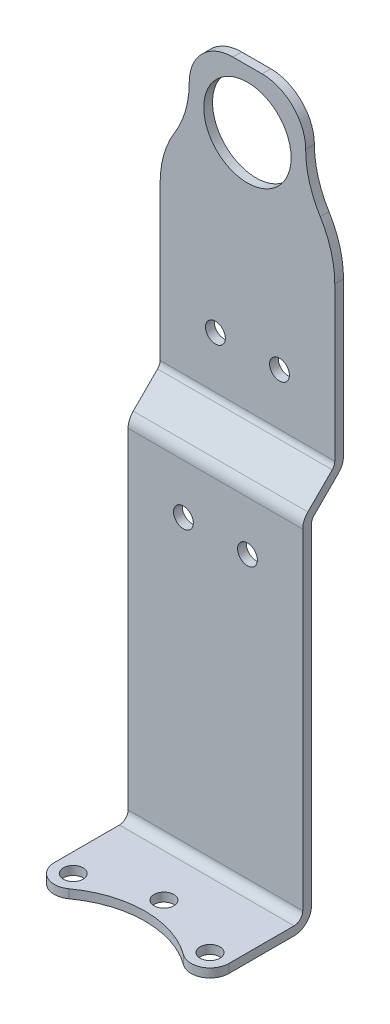
SolidWorks part; units mm, degrees
ref_plane "前视基准面" through (0, 0, 0) normal (0, 0, 1) x (1, 0, 0)
ref_plane "上视基准面" through (0, 0, 0) normal (0, 1, 0) x (1, 0, 0)
ref_plane "右视基准面" through (0, 0, 0) normal (1, 0, 0) x (0, 0, -1)
ref_plane "基准面1" through (0, -32, 0) normal (0, 1, 0) x (1, 0, 0)
sketch "草图1" plane through (0, -32, 0) normal (0, 1, 0) x (1, 0, 0)
  line L0 (-15, 4) -> (-15, -15.6773)
  line L1 (15, -15.6773) -> (15, 4)
  line L2 (15, 4) -> (-15, 4)
  arc A0 (-15, -15.6773) -> (-9.8358, -18.3038) centre (-11.75, -15.6773) ccw
  arc A1 (-9.8358, -18.3038) -> (9.8358, -18.3038) centre (0, -31.8) cw
  arc A2 (9.8358, -18.3038) -> (15, -15.6773) centre (11.75, -15.6773) ccw
extrude "凸台-拉伸1" add sketch "草图1" against normal blind 1.5
sketch "草图2" plane through (0, -32, 0) normal (0, 1, 0) x (-1, 0, 0)
  line L0 (15, 3) -> (15, -4)
  line L1 (15, -4) -> (-15, -4)
  line L2 (-15, -4) -> (-15, 3)
  line L3 (-15, 3) -> (15, 3)
extrude "凸台-拉伸2" add sketch "草图2" along normal blind 117
sketch "草图3" plane through (-15, 0, 0) normal (-1, 0, 0) x (0, 0, 1)
  line L0 (3, 85) -> (-2.5, 85)
  line L1 (-2.5, 85) -> (-2.5, 33)
  line L2 (-2.5, 33) -> (3, 27.5)
  line L3 (3, 27.5) -> (3, 85)
extrude "切除-拉伸1" cut sketch "草图3" against normal through all
sketch "草图4" plane through (0, 0, -2.5) normal (0, 0, 1) x (1, 0, 0)
  line L0 (-11.7954, 85) -> (-15, 85)
  line L1 (-15, 85) -> (-15, 60)
  arc A0 (-15, 60) -> (-12.5, 68.75) centre (1.5625, 60) cw
  arc A1 (-12.5, 68.75) -> (-11.7954, 85) centre (-26.5625, 77.5) ccw
extrude "切除-拉伸2" cut sketch "草图4" against normal through all
sketch "草图5" plane through (0, 0, -2.5) normal (0, 0, 1) x (1, 0, 0)
  line L0 (15, 85) -> (11.7954, 85)
  line L1 (15, 60) -> (15, 85)
  arc A0 (11.7954, 85) -> (12.5, 68.75) centre (26.5625, 77.5) ccw
  arc A1 (12.5, 68.75) -> (15, 60) centre (-1.5625, 60) cw
extrude "切除-拉伸3" cut sketch "草图5" against normal through all
sketch "草图6" plane through (-15, 0, 0) normal (-1, 0, 0) x (0, 0, 1)
  line L0 (1.5, -33.5) -> (1.5, 26.8787)
  line L1 (1.5, 26.8787) -> (-4, 32.3787)
  line L2 (-4, 32.3787) -> (-4, -33.5)
  line L3 (-4, -33.5) -> (1.5, -33.5)
extrude "切除-拉伸4" cut sketch "草图6" against normal through all
hole_wizard "Ø3.4 (3.4) 直径孔1" positions "草图8" profile "草图7" hole size "Ø3.4" standard "ANSI Metric"
sketch "草图8" plane through (0, 0, 3) normal (0, 0, 1) x (1, 0, 0)
  point P0 (-5.5, 17.7574)
  point P1 (5.5, 17.7574)
sketch "草图7" plane through (-5.5, 17.7574, 3) normal (1, 0, 0) x (0, -1, 0)
  line L0 (0, 0) -> (0, 7)
  line L1 (0, 7) -> (1.7, 7)
  line L2 (1.7, 7) -> (1.7, 0)
  line L5 (1.7, 0) -> (0, 0)
  line L11 (0, -6.35) -> (0, 107.95) construction
  dimension "通孔孔直径" = 3.4
  dimension "通孔孔深度" = 7
hole_wizard "Ø3.4 (3.4) 直径孔2" positions "草图10" profile "草图9" hole size "Ø3.4" standard "ANSI Metric"
sketch "草图10" plane through (0, 0, -2.5) normal (0, 0, 1) x (1, 0, 0)
  point P0 (-5.5, 42.5)
  point P1 (5.5, 42.5)
sketch "草图9" plane through (-5.5, 42.5, -2.5) normal (1, 0, 0) x (0, -1, 0)
  line L0 (0, 0) -> (0, 1.5)
  line L1 (0, 1.5) -> (1.7, 1.5)
  line L2 (1.7, 1.5) -> (1.7, 0)
  line L5 (1.7, 0) -> (0, 0)
  line L11 (0, -6.35) -> (0, 107.95) construction
  dimension "通孔孔直径" = 3.4
  dimension "通孔孔深度" = 1.5
hole_wizard "Ø3.4 (3.4) 直径孔3" positions "草图12" profile "草图11" hole size "Ø3.4" standard "ANSI Metric"
sketch "草图12" plane through (0, -32, 0) normal (0, 1, 0) x (1, 0, 0)
  point P0 (-11.75, -15.6773)
  point P1 (0, -11.85)
  point P2 (11.75, -15.6773)
sketch "草图11" plane through (-11.75, -32, 15.6773) normal (1, 0, 0) x (0, 0, 1)
  line L0 (0, 0) -> (0, 1.5)
  line L1 (0, 1.5) -> (1.7, 1.5)
  line L2 (1.7, 1.5) -> (1.7, 0)
  line L5 (1.7, 0) -> (0, 0)
  line L11 (0, -6.35) -> (0, 107.95) construction
  dimension "通孔孔直径" = 3.4
  dimension "通孔孔深度" = 1.5
hole_wizard "Ø15.0 (15) 直径孔1" positions "草图14" profile "草图13" hole size "Ø15.0" standard "ANSI Metric"
sketch "草图14" plane through (0, 0, -2.5) normal (0, 0, 1) x (1, 0, 0)
  point P0 (0, 75)
sketch "草图13" plane through (0, 75, -2.5) normal (1, 0, 0) x (0, -1, 0)
  line L0 (0, 0) -> (0, 1.5)
  line L1 (0, 1.5) -> (7.5, 1.5)
  line L2 (7.5, 1.5) -> (7.5, 0)
  line L5 (7.5, 0) -> (0, 0)
  line L11 (0, -6.35) -> (0, 107.95) construction
  dimension "通孔孔直径" = 15
  dimension "通孔孔深度" = 1.5
fillet "圆角1" radius 1.5 3 edges at (0, -32, 3) (0, 33, -2.5) (0, 26.8787, 1.5)
fillet "圆角2" radius 3 3 edges at (0, 32.3787, -4) (0, 27.5, 3) (0, -33.5, 1.5)
fillet "圆角3" radius 7.5 2 edges at (11.7954, 85, -3.25) (-11.7954, 85, -3.25)
